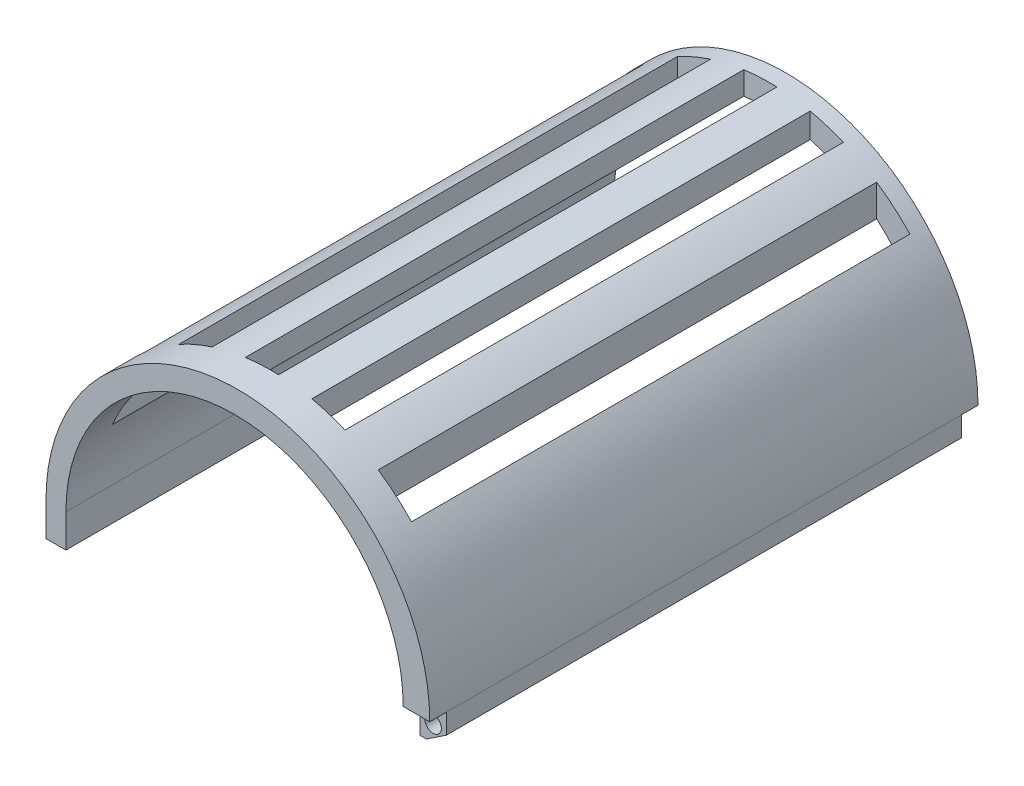
SolidWorks part; units mm, degrees
ref_plane "前基準面" through (0, 0, 0) normal (0, 0, 1) x (1, 0, 0)
ref_plane "上基準面" through (0, 0, 0) normal (0, 1, 0) x (1, 0, 0)
ref_plane "右基準面" through (0, 0, 0) normal (1, 0, 0) x (0, 0, -1)
sketch "草圖1" plane through (0, 0, 0) normal (0, 0, 1) x (1, 0, 0)
  line L0 (-57.75, 0) -> (-51.75, 0) construction
  line L1 (-57.75, 0) -> (-57.75, -10)
  line L2 (-57.75, -10) -> (-51.75, -10)
  line L3 (-51.75, -10) -> (-51.75, 0)
  line L4 (49.75, 0) -> (57.75, 0)
  line L5 (49.75, 0) -> (57.75, 0) construction
  arc A0 (57.75, 0) -> (-57.75, 0) centre (0, 0) ccw
  arc A2 (-51.75, 0) -> (49.75, 0) centre (-1, 0) cw
  dimension "D1" = 57.75
  dimension "D2" = 10
  dimension "D3" = 6
  dimension "D4" = 8
extrude "填料-伸長1" add sketch "草圖1" along normal blind 165
sketch "草圖2" plane through (0, 0, 0) normal (0, 1, 0) x (1, 0, 0)
  line L0 (57.75, 0) -> (-57.75, 0) construction
  line L1 (-47.75, -5) -> (-37.75, -5)
  line L2 (-47.75, -5) -> (-47.75, -155)
  line L3 (-47.75, -155) -> (-37.75, -155)
  line L4 (-37.75, -5) -> (-37.75, -155)
  line L5 (-47.75, -5) -> (-37.75, -155) construction
  line L6 (-47.75, -155) -> (-37.75, -5) construction
  line L7 (-42.75, -80) -> (81.8961, -80) construction
  line L8 (-57.75, -165) -> (-57.75, 0) construction
  line L9 (-27.75, -5) -> (-27.75, -155)
  line L10 (-27.75, -5) -> (-17.75, -5)
  line L11 (-17.75, -5) -> (-17.75, -155)
  line L12 (-27.75, -155) -> (-17.75, -155)
  line L13 (-7.75, -5) -> (-7.75, -155)
  line L14 (-7.75, -5) -> (2.25, -5)
  line L15 (2.25, -5) -> (2.25, -155)
  line L16 (-7.75, -155) -> (2.25, -155)
  line L17 (12.25, -5) -> (12.25, -155)
  line L18 (12.25, -5) -> (22.25, -5)
  line L19 (22.25, -5) -> (22.25, -155)
  line L20 (12.25, -155) -> (22.25, -155)
  line L21 (32.25, -5) -> (32.25, -155)
  line L22 (32.25, -5) -> (42.25, -5)
  line L23 (42.25, -5) -> (42.25, -155)
  line L24 (32.25, -155) -> (42.25, -155)
  line L25 (-57.75, -165) -> (57.75, -165) construction
  point P0 (-42.75, -80)
  dimension "D1" = 10
  dimension "D2" = 5
  dimension "D3" = 10
  dimension "D4" = 10
  dimension "D5" = 5
extrude "除料-伸長1" cut sketch "草圖2" along normal through all
sketch "草圖3" plane through (0, 0, 0) normal (0, -1, 0) x (1, 0, 0)
  line L0 (49.75, 160) -> (57.75, 160)
  line L1 (49.75, 165) -> (49.75, 0) construction
  line L2 (57.75, 165) -> (57.75, 0) construction
  line L3 (57.75, 160) -> (57.75, 5)
  line L4 (57.75, 5) -> (49.75, 5)
  line L5 (49.75, 5) -> (49.75, 160)
  line L6 (49.75, 0) -> (57.75, 0) construction
  line L7 (49.75, 165) -> (57.75, 165) construction
  dimension "D1" = 5
  dimension "D2" = 5
extrude "填料-伸長2" add sketch "草圖3" along normal blind 10
sketch "草圖4" plane through (0, 0, 160) normal (0, 0, 1) x (1, 0, 0)
  line L0 (49.75, 0) -> (57.75, 0) construction
  line L1 (57.75, -10) -> (57.75, 0) construction
  circle A0 centre (53.75, -5) radius 2.5
  dimension "D1" = 5
  dimension "D2" = 5
  dimension "D3" = 4
extrude "除料-伸長2" cut sketch "草圖4" against normal through all
sketch "草圖5" plane through (-57.75, 0, 0) normal (-1, 0, 0) x (0, 0, 1)
  line L0 (72.5, -10) -> (72.5, -7)
  line L1 (165, -10) -> (0, -10) construction
  line L2 (72.5, -7) -> (92.5, -7)
  line L3 (92.5, -7) -> (92.5, -10)
  line L4 (92.5, -10) -> (72.5, -10)
  point P4 (82.5, -10)
  dimension "D1" = 3
  dimension "D2" = 20
extrude "填料-伸長3" add sketch "草圖5" along normal blind 10
sketch "草圖6" plane through (0, 0, 160) normal (0, 0, 1) x (1, 0, 0)
  line L0 (57.75, -10) -> (57.75, -6)
  line L2 (57.75, -6) -> (51.75, -10)
  line L4 (51.75, -10) -> (57.75, -10)
  dimension "D1" = 4
  dimension "D2" = 6
extrude "除料-伸長3" cut sketch "草圖6" against normal through all
